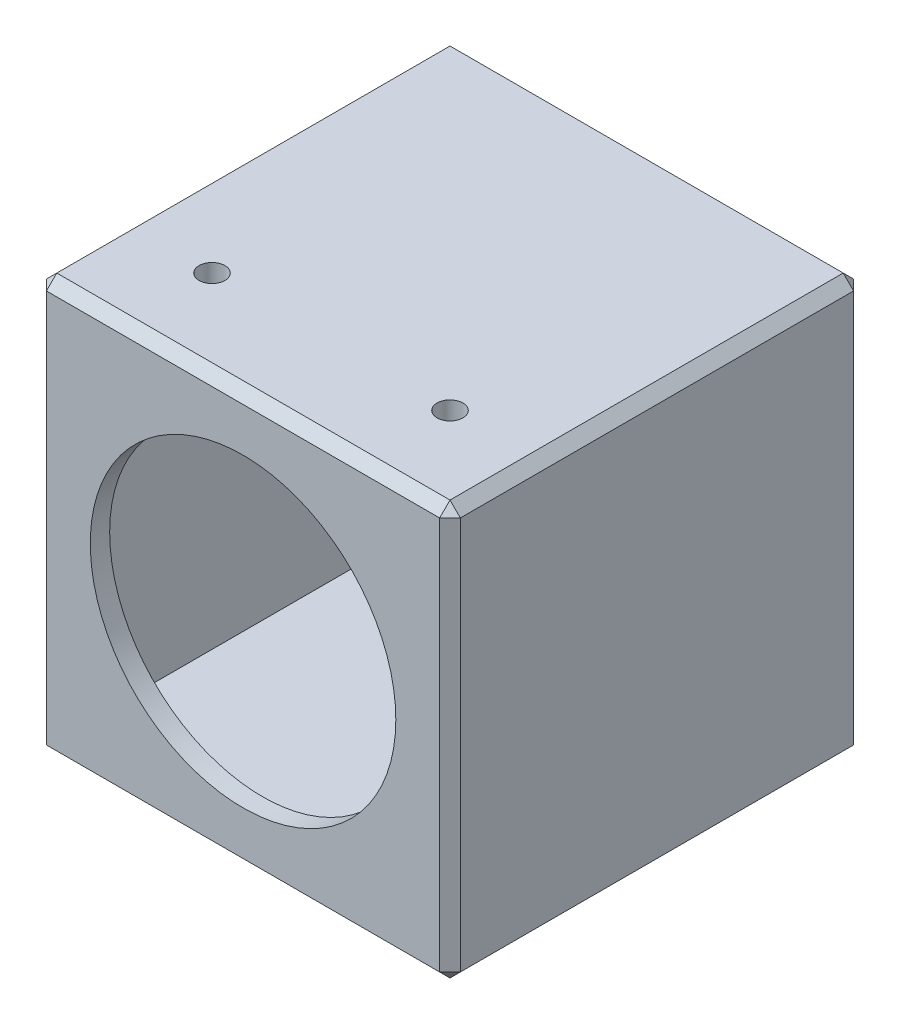
SolidWorks part; units mm, degrees
ref_plane "Front Plane" through (0, 0, 0) normal (0, 0, 1) x (1, 0, 0)
ref_plane "Top Plane" through (0, 0, 0) normal (0, 1, 0) x (1, 0, 0)
ref_plane "Right Plane" through (0, 0, 0) normal (1, 0, 0) x (0, 0, -1)
sketch "Sketch1" plane through (0, 0, 0) normal (0, 1, 0) x (1, 0, 0)
  line L1 (-50.8, 50.8) -> (50.8, 50.8)
  line L2 (-50.8, 50.8) -> (-50.8, -50.8)
  line L3 (-50.8, -50.8) -> (50.8, -50.8)
  line L4 (50.8, 50.8) -> (50.8, -50.8)
  point P4 (-50.8, 0)
  point P6 (0, 50.8)
  dimension "D1" = 101.6
  dimension "D2" = 101.6
extrude "Boss-Extrude1" add sketch "Sketch1" along normal blind 101.6
chamfer "Chamfer1" distance 2.54 angle 45 12 edges at (0, 101.6, 50.8) (0, 0, 50.8) (0, 101.6, -50.8) (-50.8, 50.8, -50.8) (-50.8, 101.6, 0) (-50.8, 50.8, 50.8) (-50.8, 0, 0) (0, 0, -50.8) (50.8, 50.8, 50.8) (50.8, 101.6, 0) (50.8, 50.8, -50.8) (50.8, 0, 0)
shell "Shell1" thickness 4.7625
sketch "Sketch2" plane through (0, 0, 50.8) normal (0, 0, 1) x (1, 0, 0)
  line L0 (-48.26, 99.06) -> (-48.26, 2.54) construction
  line L1 (48.26, 99.06) -> (-48.26, 99.06) construction
  circle A0 centre (0, 50.8) radius 37.5
  point P4 (-48.26, 50.8)
  point P7 (0, 99.06)
  dimension "D1" = 75
extrude "Cut-Extrude1" cut sketch "Sketch2" against normal up to next
sketch "Sketch3" plane through (0, 101.6, 0) normal (0, 1, 0) x (1, 0, 0)
  line L0 (-48.26, 48.26) -> (-48.26, -48.26) construction
  line L1 (48.26, -48.26) -> (48.26, 48.26) construction
  line L2 (-48.26, -48.26) -> (48.26, -48.26) construction
  circle A0 centre (-29.21, -29.21) radius 3.175
  circle A1 centre (29.21, -29.21) radius 3.175
  dimension "D1" = 6.35
  dimension "D2" = 6.35
  dimension "D3" = 19.05
  dimension "D4" = 19.05
  dimension "D5" = 19.05
extrude "Cut-Extrude2" cut sketch "Sketch3" against normal up to next
